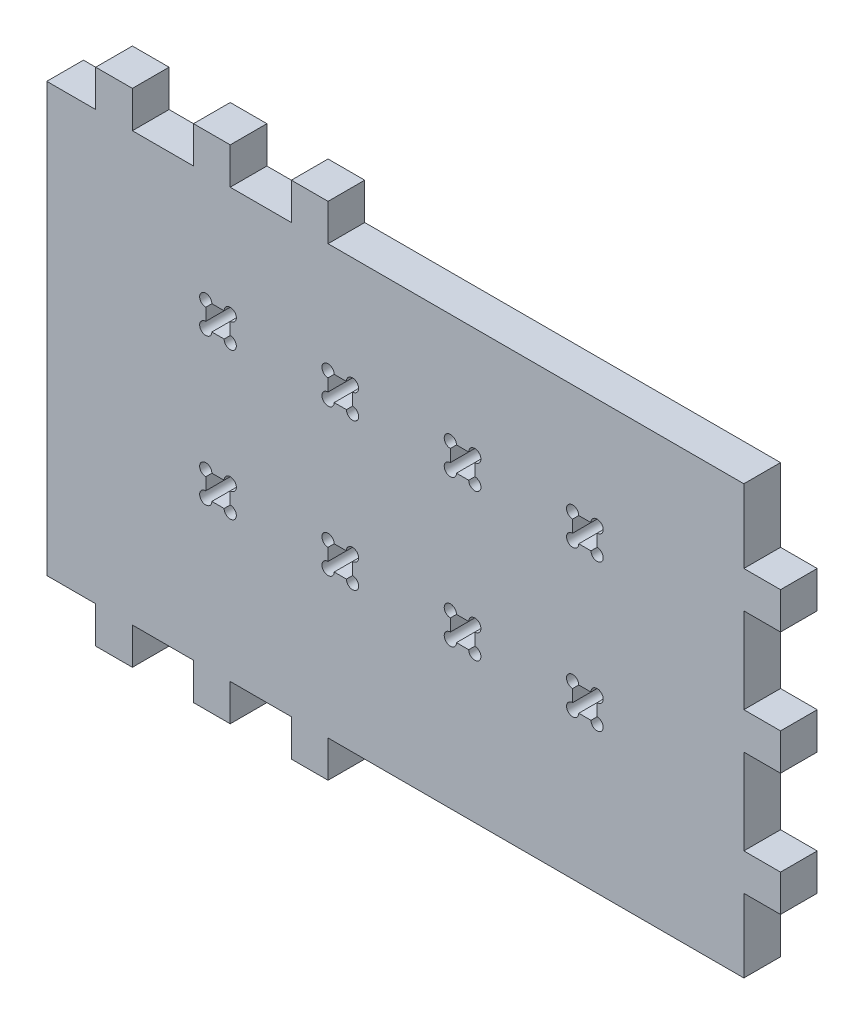
SolidWorks part; units mm, degrees
material "Balsa"
ref_plane "Front Plane" through (0, 0, 0) normal (0, 0, 1) x (1, 0, 0)
ref_plane "Top Plane" through (0, 0, 0) normal (0, 1, 0) x (1, 0, 0)
ref_plane "Right Plane" through (0, 0, 0) normal (1, 0, 0) x (0, 0, -1)
sketch "Sketch1" plane through (0, 0, 0) normal (0, 0, 1) x (1, 0, 0)
  line L1 (0, 0) -> (361.95, 0)
  line L2 (0, 0) -> (0, 222.25)
  line L3 (0, 222.25) -> (361.95, 222.25)
  line L4 (361.95, 0) -> (361.95, 222.25)
  dimension "D1" = 361.95
  dimension "D2" = 222.25
extrude "Boss-Extrude1" add sketch "Sketch1" against normal blind 19.05
sketch "Sketch2" plane through (0, 0, 0) normal (0, 0, 1) x (1, 0, 0)
  line L0 (0, 152.4) -> (361.95, 152.4)
  line L3 (0, 82.55) -> (361.95, 82.55)
  line L4 (0, 12.7) -> (361.95, 12.7) construction
  line L6 (0, 0) -> (361.95, 0) construction
  line L7 (0, 222.25) -> (0, 0) construction
  line L8 (361.95, 0) -> (361.95, 222.25) construction
  line L9 (0, 152.4) -> (-25.4, 152.4)
  line L10 (0, 82.55) -> (-25.4, 82.55)
  line L11 (0, 12.7) -> (-25.4, 12.7) construction
  line L12 (361.95, 12.7) -> (387.35, 12.7) construction
  line L13 (361.95, 82.55) -> (387.35, 82.55)
  line L14 (361.95, 152.4) -> (387.35, 152.4)
  dimension "D1" = 69.85
  dimension "D2" = 69.85
  dimension "D3" = 69.85
  dimension "5" = 0
  dimension "D4" = 25.4
  dimension "D5" = 12.7
sketch "Sketch3" plane through (0, 0, 0) normal (0, 0, 1) x (1, 0, 0)
  line L0 (44.45, 241.3) -> (76.2, 241.3) construction
  line L5 (95.25, 241.3) -> (127, 241.3) construction
  line L10 (361.95, 222.25) -> (0, 222.25) construction
  line L11 (25.4, 222.25) -> (44.45, 222.25)
  line L12 (25.4, 222.25) -> (25.4, 241.3)
  line L13 (25.4, 241.3) -> (44.45, 241.3)
  line L14 (44.45, 222.25) -> (44.45, 241.3)
  line L16 (0, 222.25) -> (0, 0) construction
  line L18 (76.2, 222.25) -> (95.25, 222.25)
  line L19 (76.2, 222.25) -> (76.2, 241.3)
  line L20 (76.2, 241.3) -> (95.25, 241.3)
  line L21 (95.25, 222.25) -> (95.25, 241.3)
  line L22 (146.05, 222.25) -> (127, 222.25)
  line L23 (146.05, 222.25) -> (146.05, 241.3)
  line L24 (146.05, 241.3) -> (127, 241.3)
  line L25 (127, 222.25) -> (127, 241.3)
  dimension "D1" = 19.05
  dimension "D2" = 25.4
  dimension "D3" = 127
extrude "Boss-Extrude4" add sketch "Sketch3" along direction (0, 0, -1) on the side against the normal up to surface (19.05 mm away)
ref_plane "Plane1" through (0, 111.125, 0) normal (0, 1, 0) x (1, 0, 0)
mirror "Mirror1" about plane through (0, 111.125, 0) normal (0, 1, 0) of "Boss-Extrude4"
ref_plane "Plane2" through (0, 0, -9.525) normal (0, 0, 1) x (1, 0, 0)
sketch "Sketch5" plane through (0, 0, 0) normal (0, 0, 1) x (1, 0, 0)
  line L0 (361.95, 0) -> (361.95, 222.25) construction
  line L1 (361.95, 184.15) -> (381, 184.15)
  line L2 (361.95, 184.15) -> (361.95, 165.1)
  line L3 (361.95, 165.1) -> (381, 165.1)
  line L4 (381, 184.15) -> (381, 165.1)
  line L5 (361.95, 0) -> (361.95, 222.25) construction
  line L6 (361.95, 38.1) -> (381, 38.1)
  line L7 (361.95, 38.1) -> (361.95, 57.15)
  line L8 (361.95, 57.15) -> (381, 57.15)
  line L9 (381, 38.1) -> (381, 57.15)
  line L10 (361.95, 222.25) -> (361.95, 184.15) construction
  line L11 (361.95, 0) -> (361.95, 38.1) construction
  line L12 (361.95, 0) -> (361.95, 222.25) construction
  line L13 (361.95, 120.65) -> (381, 120.65)
  line L14 (361.95, 120.65) -> (361.95, 101.6)
  line L15 (361.95, 101.6) -> (381, 101.6)
  line L16 (381, 120.65) -> (381, 101.6)
  dimension "D1" = 19.05
  dimension "D2" = 38.1
  dimension "D3" = 44.45
  dimension "D4" = 38.1
extrude "Boss-Extrude5" add sketch "Sketch5" against normal up to surface (19.05 mm away) up to face at (99.3321, 111.125, -19.05)
sketch "Sketch6" plane through (0, 0, 0) normal (0, 0, 1) x (1, 0, 0)
  line L0 (0, 222.25) -> (0, 0) construction
  line L1 (85.725, 88.9) -> (92.075, 88.9)
  line L2 (82.55, 85.725) -> (82.55, 79.375)
  line L3 (85.725, 76.2) -> (92.075, 76.2)
  line L4 (95.25, 85.725) -> (95.25, 79.375)
  line L5 (0, 0) -> (25.4, 0) construction
  line L28 (149.225, 76.2) -> (155.575, 76.2)
  line L63 (158.75, 85.725) -> (158.75, 79.375)
  line L64 (149.225, 88.9) -> (155.575, 88.9)
  line L65 (44.45, -19.05) -> (25.4, -19.05) construction
  line L66 (146.05, 85.725) -> (146.05, 79.375)
  line L67 (212.725, 76.2) -> (219.075, 76.2)
  line L68 (222.25, 85.725) -> (222.25, 79.375)
  line L69 (212.725, 88.9) -> (219.075, 88.9)
  line L70 (209.55, 85.725) -> (209.55, 79.375)
  line L71 (276.225, 76.2) -> (282.575, 76.2)
  line L72 (285.75, 85.725) -> (285.75, 79.375)
  line L73 (276.225, 88.9) -> (282.575, 88.9)
  line L74 (273.05, 85.725) -> (273.05, 79.375)
  line L75 (149.225, 152.4) -> (155.575, 152.4)
  line L76 (158.75, 161.925) -> (158.75, 155.575)
  line L77 (149.225, 165.1) -> (155.575, 165.1)
  line L78 (146.05, 161.925) -> (146.05, 155.575)
  line L79 (212.725, 152.4) -> (219.075, 152.4)
  line L80 (222.25, 161.925) -> (222.25, 155.575)
  line L81 (212.725, 165.1) -> (219.075, 165.1)
  line L82 (209.55, 161.925) -> (209.55, 155.575)
  line L83 (276.225, 152.4) -> (282.575, 152.4)
  line L84 (285.75, 161.925) -> (285.75, 155.575)
  line L85 (276.225, 165.1) -> (282.575, 165.1)
  line L86 (273.05, 161.925) -> (273.05, 155.575)
  line L87 (85.725, 152.4) -> (92.075, 152.4)
  line L88 (95.25, 161.925) -> (95.25, 155.575)
  line L89 (85.725, 165.1) -> (92.075, 165.1)
  line L90 (82.55, 161.925) -> (82.55, 155.575)
  line L91 (82.55, 79.375) -> (146.05, 79.375) construction
  line L92 (82.55, 79.375) -> (82.55, 155.575) construction
  arc A20 (85.725, 88.9) -> (82.55, 85.725) centre (82.55, 88.9) ccw
  arc A21 (95.25, 85.725) -> (92.075, 88.9) centre (95.25, 88.9) ccw
  arc A22 (82.55, 79.375) -> (85.725, 76.2) centre (82.55, 76.2) ccw
  arc A23 (92.075, 76.2) -> (95.25, 79.375) centre (95.25, 76.2) ccw
  arc A24 (146.05, 79.375) -> (149.225, 76.2) centre (146.05, 76.2) ccw
  arc A25 (155.575, 76.2) -> (158.75, 79.375) centre (158.75, 76.2) ccw
  arc A26 (158.75, 85.725) -> (155.575, 88.9) centre (158.75, 88.9) ccw
  arc A27 (149.225, 88.9) -> (146.05, 85.725) centre (146.05, 88.9) ccw
  arc A28 (209.55, 79.375) -> (212.725, 76.2) centre (209.55, 76.2) ccw
  arc A29 (219.075, 76.2) -> (222.25, 79.375) centre (222.25, 76.2) ccw
  arc A30 (222.25, 85.725) -> (219.075, 88.9) centre (222.25, 88.9) ccw
  arc A31 (212.725, 88.9) -> (209.55, 85.725) centre (209.55, 88.9) ccw
  arc A32 (273.05, 79.375) -> (276.225, 76.2) centre (273.05, 76.2) ccw
  arc A33 (282.575, 76.2) -> (285.75, 79.375) centre (285.75, 76.2) ccw
  arc A34 (285.75, 85.725) -> (282.575, 88.9) centre (285.75, 88.9) ccw
  arc A35 (276.225, 88.9) -> (273.05, 85.725) centre (273.05, 88.9) ccw
  arc A36 (146.05, 155.575) -> (149.225, 152.4) centre (146.05, 152.4) ccw
  arc A37 (155.575, 152.4) -> (158.75, 155.575) centre (158.75, 152.4) ccw
  arc A38 (158.75, 161.925) -> (155.575, 165.1) centre (158.75, 165.1) ccw
  arc A39 (149.225, 165.1) -> (146.05, 161.925) centre (146.05, 165.1) ccw
  arc A40 (209.55, 155.575) -> (212.725, 152.4) centre (209.55, 152.4) ccw
  arc A41 (219.075, 152.4) -> (222.25, 155.575) centre (222.25, 152.4) ccw
  arc A42 (222.25, 161.925) -> (219.075, 165.1) centre (222.25, 165.1) ccw
  arc A43 (212.725, 165.1) -> (209.55, 161.925) centre (209.55, 165.1) ccw
  arc A44 (273.05, 155.575) -> (276.225, 152.4) centre (273.05, 152.4) ccw
  arc A45 (282.575, 152.4) -> (285.75, 155.575) centre (285.75, 152.4) ccw
  arc A46 (285.75, 161.925) -> (282.575, 165.1) centre (285.75, 165.1) ccw
  arc A47 (276.225, 165.1) -> (273.05, 161.925) centre (273.05, 165.1) ccw
  arc A48 (82.55, 155.575) -> (85.725, 152.4) centre (82.55, 152.4) ccw
  arc A49 (92.075, 152.4) -> (95.25, 155.575) centre (95.25, 152.4) ccw
  arc A50 (95.25, 161.925) -> (92.075, 165.1) centre (95.25, 165.1) ccw
  arc A51 (85.725, 165.1) -> (82.55, 161.925) centre (82.55, 165.1) ccw
  dimension "D10" = 76.2
  dimension "D5" = 6.35
  dimension "D1" = 82.55
  dimension "D2" = 12.7
  dimension "D3" = 12.7
  dimension "D4" = 76.2
  dimension "D6" = 4
  dimension "D8" = 90
  dimension "D9" = 63.5
  dimension "D7" = 2
extrude "Cut-Extrude2" cut sketch "Sketch6" against normal through all both
equation "\"ShelfSpacing\"=2.75"
equation "\"D1@Sketch2\"=\"ShelfSpacing\""
equation "\"D2@Sketch2\"=\"ShelfSpacing\""
equation "\"D3@Sketch2\"=\"ShelfSpacing\""
